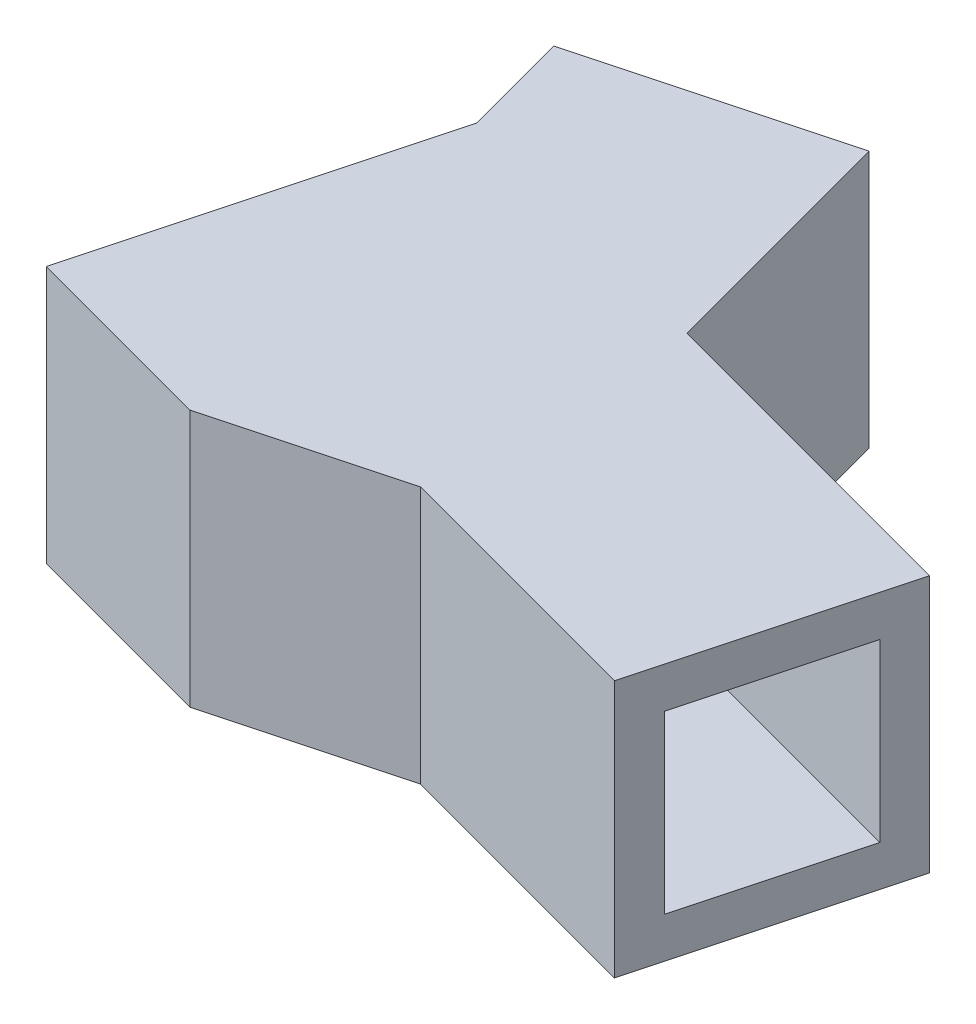
SolidWorks part; units mm, degrees
ref_plane "Спереди" through (0, 0, 0) normal (0, 0, 1) x (1, 0, 0)
ref_plane "Сверху" through (0, 0, 0) normal (0, 1, 0) x (1, 0, 0)
ref_plane "Справа" through (0, 0, 0) normal (1, 0, 0) x (0, 0, -1)
sketch "Sketch1" plane through (0, 0, 0) normal (0, 1, 0) x (1, 0, 0)
  line L0 (-19.3185, 10.3528) -> (-15.4362, -4.1361) construction
  line L1 (0, 0) -> (15.4362, -4.1361)
  line L2 (15.4362, -4.1361) -> (19.3185, 10.3528)
  line L3 (19.3185, 10.3528) -> (0, 15.5291)
  line L4 (0, 15.5291) -> (-19.3185, 10.3528) construction
  line L5 (-15.4362, -4.1361) -> (0, 0) construction
  line L6 (0, 0) -> (0, 15.5291) construction
  line L7 (0, 15.5291) -> (-3.8823, 30.018)
  line L8 (-3.8823, 30.018) -> (-18.3712, 26.1357)
  line L9 (-18.3712, 26.1357) -> (-10.6066, -2.842)
  line L10 (-10.6066, -2.842) -> (0, 0)
  dimension "D1" = 150
  dimension "D2" = 15
  dimension "D3" = 20
  dimension "D4" = 15
  dimension "D5" = 30
extrude "Boss-Extrude1" add sketch "Sketch1" along normal blind 15
sketch "Sketch2" plane through (15.4362, 0, 4.1361) normal (0.9659, 0, 0.2588) x (0.2588, 0, -0.9659)
  line L0 (15, 7.5) -> (0, 7.5) construction
  line L1 (15, 15) -> (15, 0) construction
  line L2 (0, 15) -> (0, 0) construction
  line L4 (2.375, 2.375) -> (12.625, 2.375)
  line L5 (2.375, 2.375) -> (2.375, 12.625)
  line L6 (2.375, 12.625) -> (12.625, 12.625)
  line L7 (12.625, 2.375) -> (12.625, 12.625)
  line L8 (2.375, 2.375) -> (12.625, 12.625) construction
  line L9 (2.375, 12.625) -> (12.625, 2.375) construction
  point P6 (7.5, 7.5)
  dimension "D1" = 10.25
extrude "Cut-Extrude1" cut sketch "Sketch2" against normal blind 18
sketch "Sketch3" plane through (-7.7646, 0, -28.9778) normal (-0.2588, 0, -0.9659) x (-0.9659, 0, 0.2588)
  line L0 (10.9808, 7.5) -> (-4.0192, 7.5) construction
  line L1 (10.9808, 15) -> (10.9808, 0) construction
  line L2 (-4.0192, 15) -> (-4.0192, 0) construction
  line L4 (-1.6442, 12.625) -> (8.6058, 12.625)
  line L5 (-1.6442, 12.625) -> (-1.6442, 2.375)
  line L6 (-1.6442, 2.375) -> (8.6058, 2.375)
  line L7 (8.6058, 12.625) -> (8.6058, 2.375)
  line L8 (-1.6442, 12.625) -> (8.6058, 2.375) construction
  line L9 (-1.6442, 2.375) -> (8.6058, 12.625) construction
  point P6 (3.4808, 7.5)
  dimension "D1" = 10.25
extrude "Cut-Extrude2" cut sketch "Sketch3" against normal blind 17
sketch "Sketch4" plane through (-1.9504, 0, -0.5226) normal (0.9659, 0, 0.2588) x (0.2588, 0, -0.9659)
  line L0 (2.375, 12.625) -> (12.625, 2.375) construction
  line L2 (11.5, 3.5) -> (3.5, 3.5)
  line L3 (11.5, 3.5) -> (11.5, 11.5)
  line L4 (11.5, 11.5) -> (3.5, 11.5)
  line L5 (3.5, 3.5) -> (3.5, 11.5)
  line L6 (11.5, 3.5) -> (3.5, 11.5) construction
  line L7 (11.5, 11.5) -> (3.5, 3.5) construction
  point P4 (7.5, 7.5)
  dimension "D1" = 8
extrude "Cut-Extrude3" cut sketch "Sketch4" against normal up to surface (9.9386 mm away)
sketch "Sketch5" plane through (-3.3646, 0, -12.557) normal (-0.2588, 0, -0.9659) x (-0.9659, 0, 0.2588)
  line L0 (8.6058, 2.375) -> (-1.6442, 12.625) construction
  line L2 (-0.5192, 3.5) -> (7.4808, 3.5)
  line L3 (-0.5192, 3.5) -> (-0.5192, 11.5)
  line L4 (-0.5192, 11.5) -> (7.4808, 11.5)
  line L5 (7.4808, 3.5) -> (7.4808, 11.5)
  line L6 (-0.5192, 3.5) -> (7.4808, 11.5) construction
  line L7 (-0.5192, 11.5) -> (7.4808, 3.5) construction
  point P4 (3.4808, 7.5)
  dimension "D1" = 8
extrude "Cut-Extrude4" cut sketch "Sketch5" against normal up to surface (9.2583 mm away)
fillet "Fillet1" radius 6 1 edges at (-10.6445, 7.5, -6.4756)
fillet "Fillet2" radius 3 8 edges at (-0.0093, 11.5, -7.7671) (-0.0093, 3.5, -7.7671) (-9.9881, 3.5, -7.132) (-4.1715, 11.5, -4.7412) (-9.9881, 11.5, -7.132) (-0.9159, 11.5, -12.1511) (-0.9159, 3.5, -12.1511) (-4.1715, 3.5, -4.7412)
sketch "Sketch6" plane through (0, 15, 0) normal (0, 1, 0) x (1, 0, 0)
  line L0 (-10.6066, -2.842) -> (-22.0336, 0.2198)
  line L2 (-22.0336, 0.2198) -> (-16.7303, 20.012)
  line L3 (-18.3712, 26.1357) -> (-10.6066, -2.842) construction
  line L7 (-16.7303, 20.012) -> (-10.6066, -2.842)
  line L8 (15.4362, -4.1361) -> (19.3185, 10.3528) construction
  line L9 (19.3185, 10.3528) -> (0, 15.5291) construction
  point P7 (0, 0)
extrude "Boss-Extrude2" add sketch "Sketch6" against normal up to surface (15 mm away) up to face at (0.2707, 0, -10.7225)
